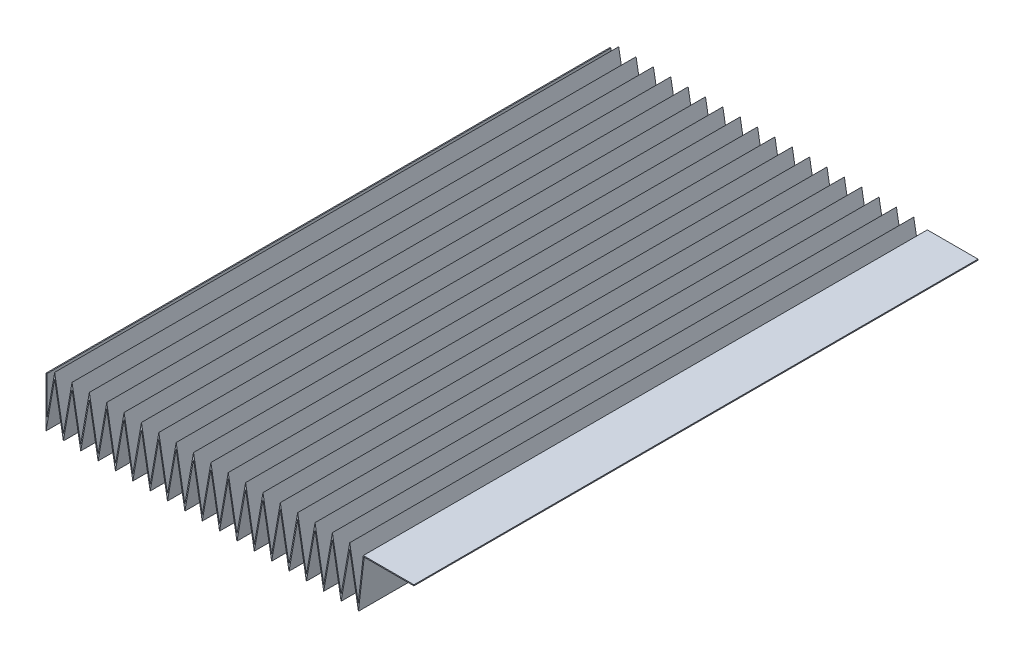
SolidWorks part; units mm, degrees
ref_plane "Front Plane" through (0, 0, 0) normal (0, 0, 1) x (1, 0, 0)
ref_plane "Top Plane" through (0, 0, 0) normal (0, 1, 0) x (1, 0, 0)
ref_plane "Right Plane" through (0, 0, 0) normal (1, 0, 0) x (0, 0, -1)
sketch "Sketch1" plane through (0, 0, 0) normal (0, 0, 1) x (1, 0, 0)
  line L0 (0, 0) -> (2.6158, 14.8717)
  line L1 (2.6158, 14.8717) -> (5.2315, 0)
  line L2 (0, 0) -> (511, 0) construction
  line L3 (5.2315, 0) -> (7.8473, 14.8717)
  line L4 (7.8473, 14.8717) -> (10.4631, 0)
  line L5 (10.4631, 0) -> (13.0788, 14.8717)
  line L6 (13.0788, 14.8717) -> (15.6946, 0)
  line L7 (15.6946, 0) -> (18.3104, 14.8717)
  line L8 (18.3104, 14.8717) -> (20.9262, 0)
  line L9 (20.9262, 0) -> (23.5419, 14.8717)
  line L10 (23.5419, 14.8717) -> (26.1577, 0)
  line L11 (26.1577, 0) -> (28.7735, 14.8717)
  line L12 (28.7735, 14.8717) -> (31.3892, 0)
  line L13 (31.3892, 0) -> (34.005, 14.8717)
  line L14 (34.005, 14.8717) -> (36.6208, 0)
  line L15 (36.6208, 0) -> (39.2365, 14.8717)
  line L16 (39.2365, 14.8717) -> (41.8523, 0)
  line L17 (41.8523, 0) -> (44.4681, 14.8717)
  line L18 (44.4681, 14.8717) -> (47.0838, 0)
  line L19 (0, 0) -> (0, 15.1)
  line L20 (47.0838, 0) -> (49.6996, 14.8717)
  line L21 (49.6996, 14.8717) -> (52.3154, 0)
  line L22 (52.3154, 0) -> (54.9311, 14.8717)
  line L23 (54.9311, 14.8717) -> (57.5469, 0)
  line L24 (57.5469, 0) -> (60.1627, 14.8717)
  line L25 (60.1627, 14.8717) -> (62.7785, 0)
  line L26 (62.7785, 0) -> (65.3942, 14.8717)
  line L27 (65.3942, 14.8717) -> (68.01, 0)
  line L28 (68.01, 0) -> (70.6258, 14.8717)
  line L29 (70.6258, 14.8717) -> (73.2415, 0)
  line L30 (73.2415, 0) -> (75.8573, 14.8717)
  line L31 (75.8573, 14.8717) -> (78.4731, 0)
  line L32 (78.4731, 0) -> (81.0888, 14.8717)
  line L33 (81.0888, 14.8717) -> (83.7046, 0)
  line L34 (83.7046, 0) -> (86.3204, 14.8717)
  line L35 (86.3204, 14.8717) -> (88.9361, 0)
  line L36 (88.9361, 0) -> (91.5519, 14.8717)
  line L37 (91.5519, 14.8717) -> (94.1677, 0)
  line L38 (94.1677, 0) -> (95.9026, 15)
  line L39 (95.9026, 15) -> (110.9026, 15)
  line L42 (112.9026, 13.6) -> (112.9026, 34.6) construction
  dimension "D1" = 511
  dimension "D2" = 15.1
  dimension "D3" = 15
  dimension "D4" = 5.2315
  dimension "D6" = 15
  dimension "D7" = 2
  dimension "D5" = 18
extrude "Extrude-Thin1" add sketch "Sketch1" along normal mid plane 170 thin thin type one direction reverse wall 0.3
